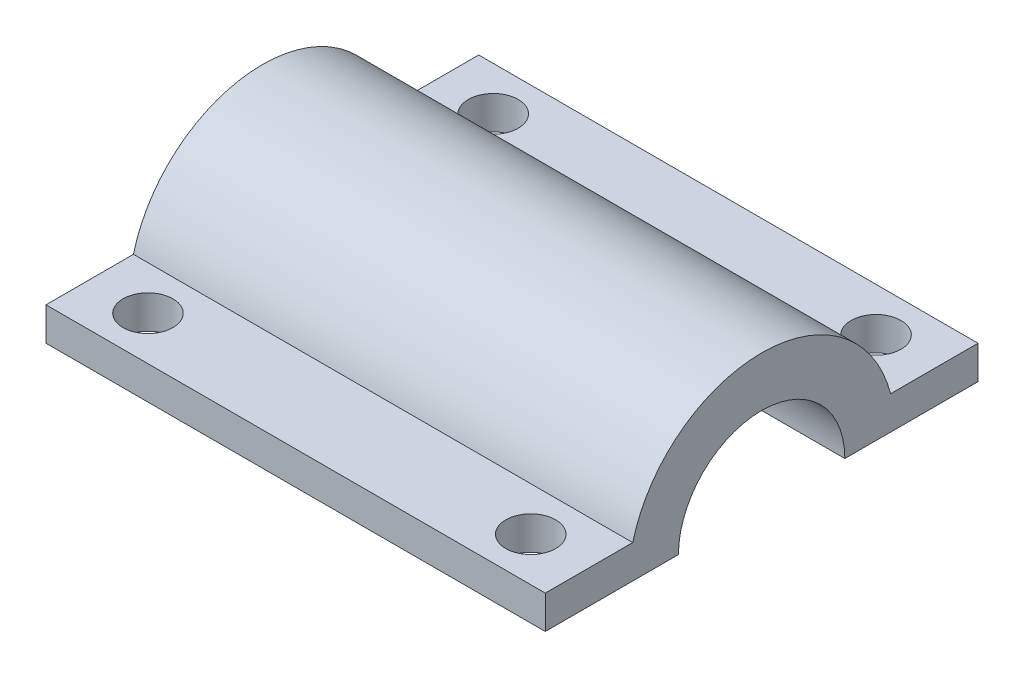
SolidWorks part; units mm, degrees
ref_plane "前视基准面" through (0, 0, 0) normal (0, 0, 1) x (1, 0, 0)
ref_plane "上视基准面" through (0, 0, 0) normal (0, 1, 0) x (1, 0, 0)
ref_plane "右视基准面" through (0, 0, 0) normal (1, 0, 0) x (0, 0, -1)
sketch "草图1" plane through (0, 0, 0) normal (1, 0, 0) x (0, 0, -1)
  line L0 (-9.1159, 0) -> (10.9527, 0) construction
  line L1 (-5, 0) -> (-13, 0)
  line L2 (-13, 0) -> (-13, 2)
  line L3 (-13, 2) -> (-7.746, 2)
  line L4 (0, -1.203) -> (0, 9.9981) construction
  line L5 (5, 0) -> (13, 0)
  line L6 (13, 0) -> (13, 2)
  line L7 (13, 2) -> (7.746, 2)
  arc A0 (5, 0) -> (-5, 0) centre (0, 0) ccw
  arc A1 (7.746, 2) -> (-7.746, 2) centre (0, 0) ccw
  dimension "D1" = 10
  dimension "D2" = 16
  dimension "D3" = 8
  dimension "D4" = 2
extrude "凸台-拉伸1" add sketch "草图1" along normal blind 30
sketch "草图2" plane through (0, 0, 0) normal (0, -1, 0) x (1, 0, 0)
  circle A0 centre (26.5, -10.373) radius 1.5
  circle A1 centre (3.5, -10.373) radius 1.5
  circle A2 centre (3.5, 10.373) radius 1.5
  circle A3 centre (26.5, 10.373) radius 1.5
extrude "切除-拉伸1" cut sketch "草图2" against normal blind 10
